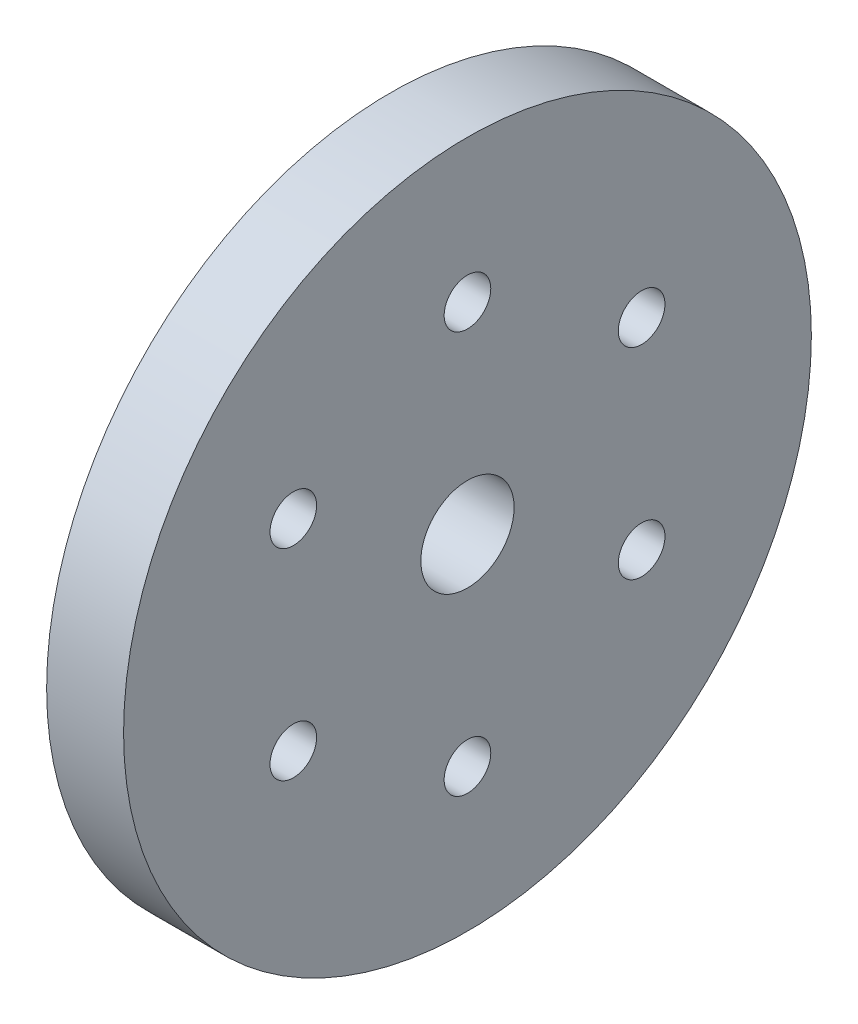
SolidWorks part; units mm, degrees
ref_plane "前视基准面" through (0, 0, 0) normal (0, 0, 1) x (1, 0, 0)
ref_plane "上视基准面" through (0, 0, 0) normal (0, 1, 0) x (1, 0, 0)
ref_plane "右视基准面" through (0, 0, 0) normal (1, 0, 0) x (0, 0, -1)
sketch "草图1" plane through (0, 0, 0) normal (1, 0, 0) x (0, 0, -1)
  circle A0 centre (0, 0) radius 29.5
  dimension "D1" = 59
extrude "凸台-拉伸1" add sketch "草图1" along normal blind 6.6
sketch "草图2" plane through (6.6, 0, 0) normal (1, 0, 0) x (0, 0, -1)
  circle A0 centre (0, 0) radius 17.25 construction
  circle A1 centre (0, 17.25) radius 2
  circle A2 centre (14.9389, 8.625) radius 2
  circle A3 centre (14.9389, -8.625) radius 2
  circle A4 centre (0, -17.25) radius 2
  circle A5 centre (-14.9389, -8.625) radius 2
  circle A6 centre (-14.9389, 8.625) radius 2
  point P17 (0, 0)
  dimension "D1" = 34.5
  dimension "D2" = 4
  dimension "D3" = 6
extrude "切除-拉伸1" cut sketch "草图2" against normal blind 6.6
sketch "草图3" plane through (6.6, 0, 0) normal (1, 0, 0) x (0, 0, -1)
  circle A0 centre (0, 0) radius 4
extrude "切除-拉伸2" cut sketch "草图3" against normal blind 6.6
